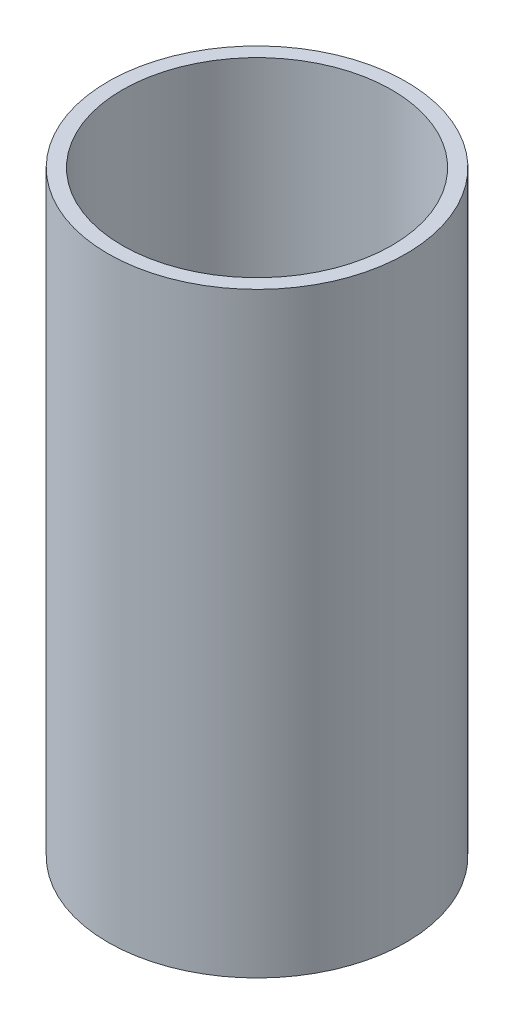
SolidWorks part; units mm, degrees
ref_plane "Front Plane" through (0, 0, 0) normal (0, 0, 1) x (1, 0, 0)
ref_plane "Top Plane" through (0, 0, 0) normal (0, 1, 0) x (1, 0, 0)
ref_plane "Right Plane" through (0, 0, 0) normal (1, 0, 0) x (0, 0, -1)
sketch "Sketch1" plane through (0, 0, 0) normal (0, 1, 0) x (1, 0, 0)
  circle A0 centre (0, 0) radius 25
  circle A1 centre (0, 0) radius 22.6
  dimension "D1" = 50
  dimension "D2" = 45.2
extrude "Boss-Extrude1" add sketch "Sketch1" along normal blind 100
